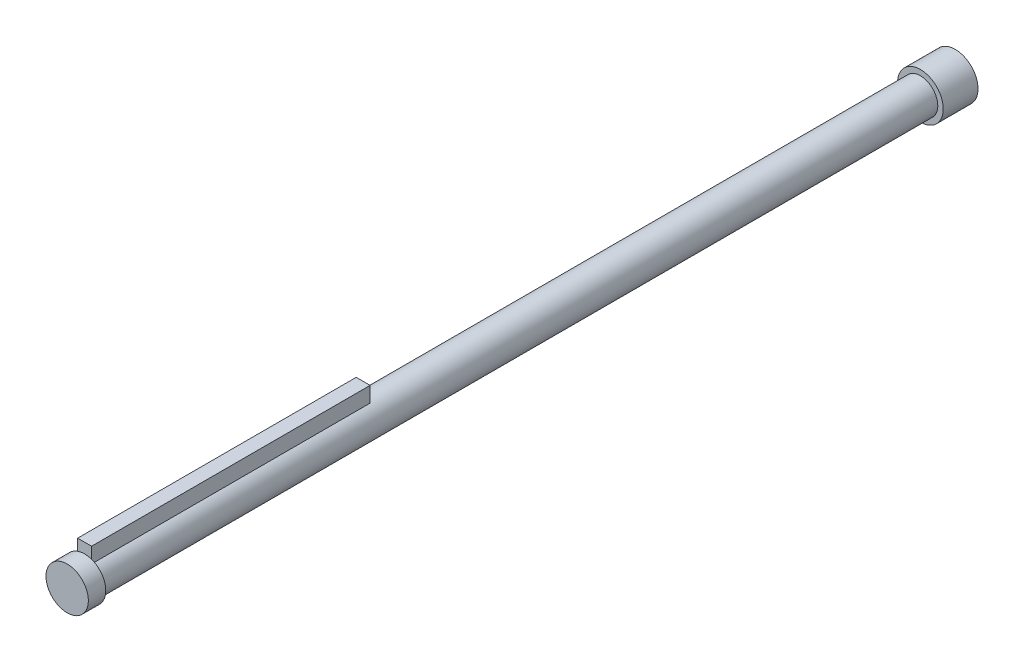
SolidWorks part; units mm, degrees
ref_plane "Front Plane" through (0, 0, 0) normal (0, 0, 1) x (1, 0, 0)
ref_plane "Top Plane" through (0, 0, 0) normal (0, 1, 0) x (1, 0, 0)
ref_plane "Right Plane" through (0, 0, 0) normal (1, 0, 0) x (0, 0, -1)
sketch "Sketch1" plane through (0, 0, 0) normal (0, 0, 1) x (1, 0, 0)
  circle A0 centre (0, 0) radius 3.175
extrude "Boss-Extrude1" add sketch "Sketch1" along normal blind 152.4 contours A0
sketch "Sketch2" plane through (0, 0, 152.4) normal (0, 0, 1) x (1, 0, 0)
  line L0 (0, -3.4925) -> (0, 3.4925) construction
  line L1 (-1.27, 5.715) -> (1.27, 5.715)
  line L2 (-1.27, 5.715) -> (-1.27, 0.635)
  line L3 (-1.27, 0.635) -> (1.27, 0.635)
  line L4 (1.27, 5.715) -> (1.27, 0.635)
  line L5 (-1.27, 5.715) -> (1.27, 0.635) construction
  line L6 (-1.27, 0.635) -> (1.27, 5.715) construction
  circle A0 centre (0, 0) radius 3.175 construction
  point P0 (0, 3.175)
extrude "Boss-Extrude4" add sketch "Sketch2" against normal blind 50.8
sketch "Sketch3" plane through (0, 0, 0) normal (0, 0, -1) x (-1, 0, 0)
  circle A0 centre (0, 0) radius 4.1626
extrude "Boss-Extrude5" add sketch "Sketch3" along normal blind 6.35
sketch "Sketch4" plane through (0, 0, 152.4) normal (0, 0, 1) x (1, 0, 0)
  circle A0 centre (0, 0) radius 3.861
extrude "Boss-Extrude6" add sketch "Sketch4" along normal blind 3.175
